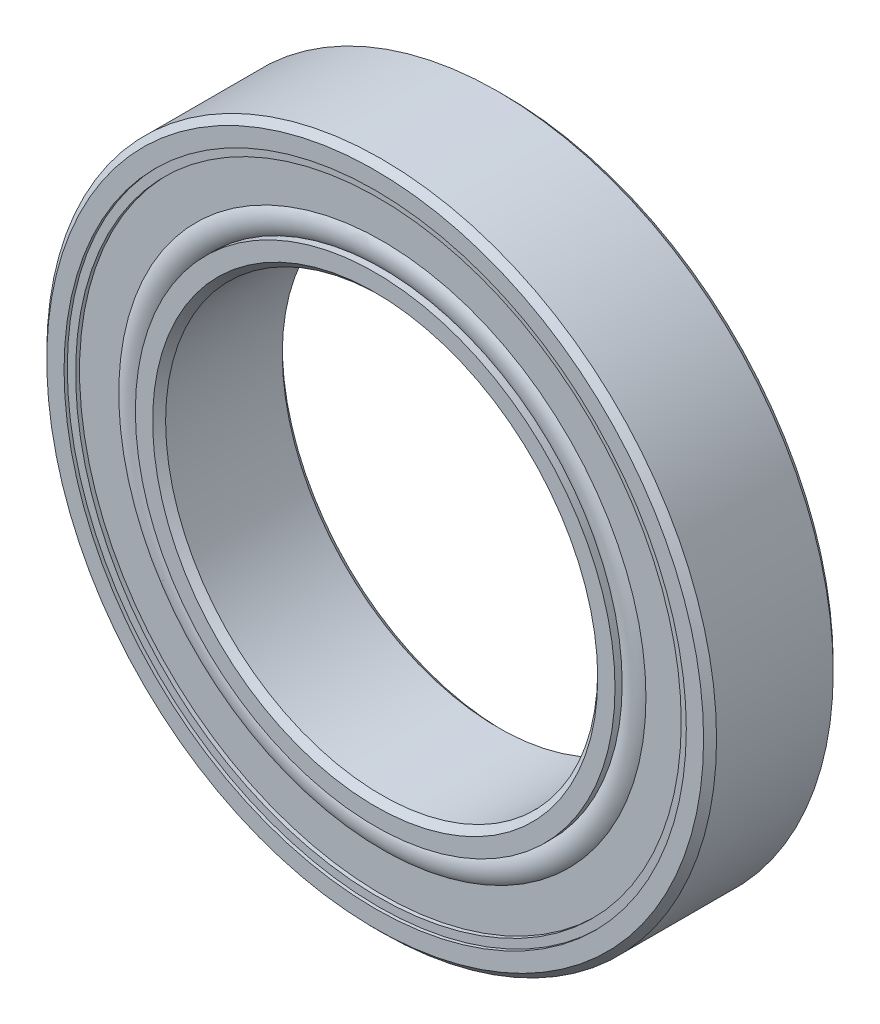
SolidWorks part; units mm, degrees
ref_plane "Front Plane" through (0, 0, 0) normal (0, 0, 1) x (1, 0, 0)
ref_plane "Top Plane" through (0, 0, 0) normal (0, 1, 0) x (1, 0, 0)
ref_plane "Right Plane" through (0, 0, 0) normal (1, 0, 0) x (0, 0, -1)
sketch "Sketch1" plane through (0, 0, 0) normal (0, 0, 1) x (1, 0, 0)
  circle A0 centre (0, 0) radius 31 construction
  circle A1 centre (0, 0) radius 19.9995 construction
  dimension "OD" = 62
  dimension "ID" = 39.999
sketch "Sketch2" plane through (0, 0, 0) normal (1, 0, 0) x (0, 0, -1)
  line L0 (-6, 0) -> (6, 0) construction
  line L1 (0, 31) -> (0, -31) construction
  line L2 (5.4, 31) -> (-5.4, 31) construction
  line L3 (-5.4, 31) -> (-6, 30.4) construction
  line L4 (-6, 30.4) -> (-6, 28.7998) construction
  line L5 (-6, 28.7998) -> (-2.6667, 28.7997) construction
  line L6 (6, 28.7998) -> (2.6667, 28.7997) construction
  line L7 (6, 30.4) -> (6, 28.7998) construction
  line L8 (5.4, 31) -> (6, 30.4) construction
  line L9 (0, 31) -> (0, 25.4998) construction
  line L10 (0, 25.4998) -> (0, 19.9995) construction
  line L11 (6, 25.4998) -> (-6, 25.4998) construction
  line L12 (-6, 20.5995) -> (-6, 22.1998) construction
  line L13 (-5.4, 19.9995) -> (-6, 20.5995) construction
  line L14 (5.4, 19.9995) -> (-5.4, 19.9995) construction
  line L15 (5.4, 19.9995) -> (6, 20.5995) construction
  line L16 (6, 20.5995) -> (6, 22.1998) construction
  line L17 (6, 22.1998) -> (2.6667, 22.1998) construction
  line L18 (-6, 22.1998) -> (-2.6667, 22.1998) construction
  line L19 (-6, 20) -> (-6, -20) construction
  line L20 (6, 31) -> (6, -31) construction
  arc A0 (-2.6667, 28.7997) -> (2.6667, 28.7997) centre (0, 25.4998) cw construction
  arc A1 (-2.6667, 22.1998) -> (2.6667, 22.1998) centre (0, 25.4998) ccw construction
  point P14 (0, 19.9995)
  point P18 (0, 25.4998)
  dimension "Approx. Ball Dia." = 8.4855
  dimension "D1" = 45
  dimension "D2" = 0.6
  dimension "D3" = 5.3333
  dimension "D4" = 3.3
  dimension "Width" = 12
  dimension "For Shaft Diameter" = 40
  dimension "For Housing ID" = 62
sketch "Sketch3" plane through (0, 0, 0) normal (1, 0, 0) x (0, 0, -1)
  line L0 (-6, 30.4) -> (-6, 28.7998) construction
  line L1 (-5.4, 31) -> (-6, 30.4) construction
  line L2 (5.4, 31) -> (-5.4, 31) construction
  line L3 (5.4, 31) -> (6, 30.4) construction
  line L4 (6, 30.4) -> (6, 28.7998) construction
  line L5 (6, 28.7998) -> (2.6667, 28.7997) construction
  line L6 (-6, 28.7998) -> (-2.6667, 28.7997) construction
  line L7 (-6, 30.4) -> (-6, 28.7998)
  line L8 (-5.4, 31) -> (-6, 30.4)
  line L9 (5.4, 31) -> (-5.4, 31)
  line L10 (5.4, 31) -> (6, 30.4)
  line L11 (6, 30.4) -> (6, 28.7998)
  line L12 (6, 28.7998) -> (2.6667, 28.7997)
  line L13 (-6, 28.7998) -> (-2.6667, 28.7997)
  line L14 (-6, 20.5995) -> (-6, 22.1998) construction
  line L15 (-5.4, 19.9995) -> (-6, 20.5995) construction
  line L16 (5.4, 19.9995) -> (-5.4, 19.9995) construction
  line L17 (5.4, 19.9995) -> (6, 20.5995) construction
  line L18 (6, 20.5995) -> (6, 22.1998) construction
  line L19 (6, 22.1998) -> (2.6667, 22.1998) construction
  line L20 (-6, 22.1998) -> (-2.6667, 22.1998) construction
  line L21 (-6, 20.5995) -> (-6, 22.1998)
  line L22 (-5.4, 19.9995) -> (-6, 20.5995)
  line L23 (5.4, 19.9995) -> (-5.4, 19.9995)
  line L24 (5.4, 19.9995) -> (6, 20.5995)
  line L25 (6, 20.5995) -> (6, 22.1998)
  line L26 (6, 22.1998) -> (2.6667, 22.1998)
  line L27 (-6, 22.1998) -> (-2.6667, 22.1998)
  arc A0 (2.6667, 28.7997) -> (-2.6667, 28.7997) centre (0, 25.4998) ccw construction
  arc A1 (2.6667, 28.7997) -> (-2.6667, 28.7997) centre (0, 25.4998) ccw
  arc A2 (-2.6667, 22.1998) -> (2.6667, 22.1998) centre (0, 25.4998) ccw construction
  arc A3 (-2.6667, 22.1998) -> (2.6667, 22.1998) centre (0, 25.4998) ccw
revolve "Revolve1" add sketch "Sketch3" angle 360 about L0
sketch "Sketch4" plane through (0, 0, 0) normal (1, 0, 0) x (0, 0, -1)
  line L0 (-4.2428, 25.4998) -> (4.2428, 25.4998)
  arc A2 (-4.2428, 25.4998) -> (4.2428, 25.4998) centre (0, 25.4998) cw
  arc A3 (2.6667, 28.7997) -> (-2.6667, 28.7997) centre (0, 25.4998) ccw construction
revolve "Revolve2" add sketch "Sketch4" angle 360 about L0
pattern_circular "CirPattern1" count 11 over 360 about axis through (0, 0, 0) along (0, 0, 1) of bodies 104
sketch "Sketch5" plane through (0, 0, 0) normal (1, 0, 0) x (0, 0, -1)
  line L0 (-6, 28.7998) -> (-2.6667, 28.7997) construction
  line L1 (-5.7, 28.7998) -> (-4.2428, 28.7997)
  line L2 (-5.7, 28.7998) -> (-5.7, 28.0298)
  line L3 (-5.7, 22.1997) -> (-4.2428, 22.1998) construction
  line L4 (-4.2428, 28.7997) -> (-4.2428, 22.1998)
  line L5 (0, 31) -> (0, 0) construction
  line L7 (-5.7, 28.0298) -> (-5.3357, 28.0298)
  line L8 (-5.3357, 28.0298) -> (-5.3357, 24.3998)
  line L9 (-5.3357, 24.3998) -> (-5.7, 24.3997) construction
  line L10 (-5.7, 24.3997) -> (-5.7, 22.1997) construction
  line L11 (5.4, 31) -> (-5.4, 31) construction
  line L12 (-5.4, 31) -> (-6, 30.4) construction
  line L13 (-6, 22.1998) -> (-2.6667, 22.1998) construction
  line L15 (-5.3357, 22.1998) -> (-4.2428, 22.1998)
  line L16 (5.7, 24.3997) -> (5.7, 22.1997) construction
  line L17 (5.3357, 24.3998) -> (5.7, 24.3997) construction
  line L18 (5.7, 22.1997) -> (4.2428, 22.1998) construction
  line L19 (5.3357, 22.1998) -> (4.2428, 22.1998)
  line L20 (5.3357, 28.0298) -> (5.3357, 24.3998)
  line L21 (5.7, 28.0298) -> (5.3357, 28.0298)
  line L22 (4.2428, 28.7997) -> (4.2428, 22.1998)
  line L23 (5.7, 28.7998) -> (5.7, 28.0298)
  line L24 (5.7, 28.7998) -> (4.2428, 28.7997)
  arc A0 (-5.3357, 22.1998) -> (-5.3357, 24.3998) centre (-3.8572, 23.2997) cw
  arc A1 (5.3357, 22.1998) -> (5.3357, 24.3998) centre (3.8572, 23.2997) ccw
  point P10 (-5.3357, 22.1998)
  point P18 (-5.7, 30.7)
  dimension "D1" = 0.77
  dimension "D2" = 2.2
  dimension "D3" = 1.4572
  dimension "D4" = 0.3643
revolve "Revolve3" add sketch "Sketch5" angle 360 about L0
equation "\"D2@Sketch2\"= \"Width@Sketch2\" * .05"
equation "\"D3@Sketch2\"=\"Width@Sketch2\" / 2.25"
equation "\"D4@Sketch2\"=( \"OD@Sketch1\" - \"For Shaft Diameter@Sketch2\" ) *0.15"
equation "\"Approx. No. of Balls\"= ( pi * \"OD@Sketch1\" ) * .5 / \"Approx. Ball Dia.@Sketch2\""
equation "\"Balls@CirPattern1\"=\"Approx. No. of Balls\""
equation "\"D1@Sketch5\"=( \"OD@Sketch1\" - \"For Shaft Diameter@Sketch2\" ) *0.035"
equation "\"D2@Sketch5\"=( \"OD@Sketch1\" - \"For Shaft Diameter@Sketch2\" ) *0.1"
equation "\"D4@Sketch5\"=\"D3@Sketch5\"*.25"
